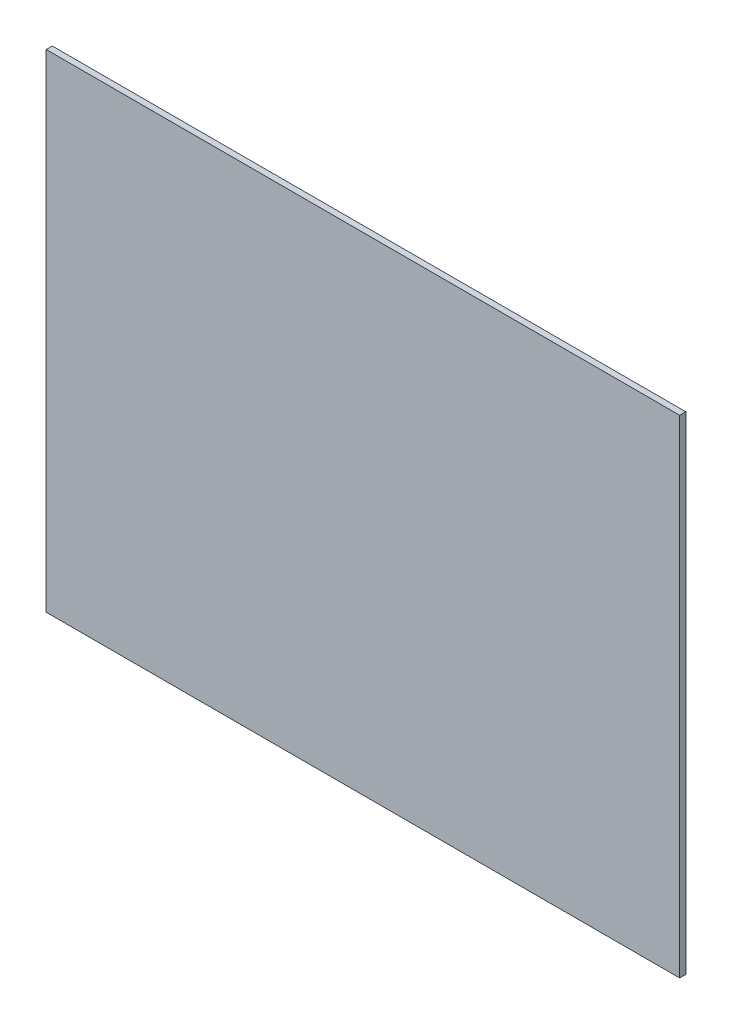
SolidWorks part; units mm, degrees
ref_plane "Front Plane" through (0, 0, 0) normal (0, 0, 1) x (1, 0, 0)
ref_plane "Top Plane" through (0, 0, 0) normal (0, 1, 0) x (1, 0, 0)
ref_plane "Right Plane" through (0, 0, 0) normal (1, 0, 0) x (0, 0, -1)
sketch "Sketch1" plane through (0, 0, 0) normal (0, 0, 1) x (1, 0, 0)
  line L1 (-32.07, 24.2769) -> (298.13, 24.2769)
  line L2 (-32.07, 24.2769) -> (-32.07, -229.7231)
  line L3 (-32.07, -229.7231) -> (298.13, -229.7231)
  line L4 (298.13, 24.2769) -> (298.13, -229.7231)
  dimension "D1" = 330.2
  dimension "D2" = 254
extrude "Boss-Extrude1" add sketch "Sketch1" along normal blind 3.175
